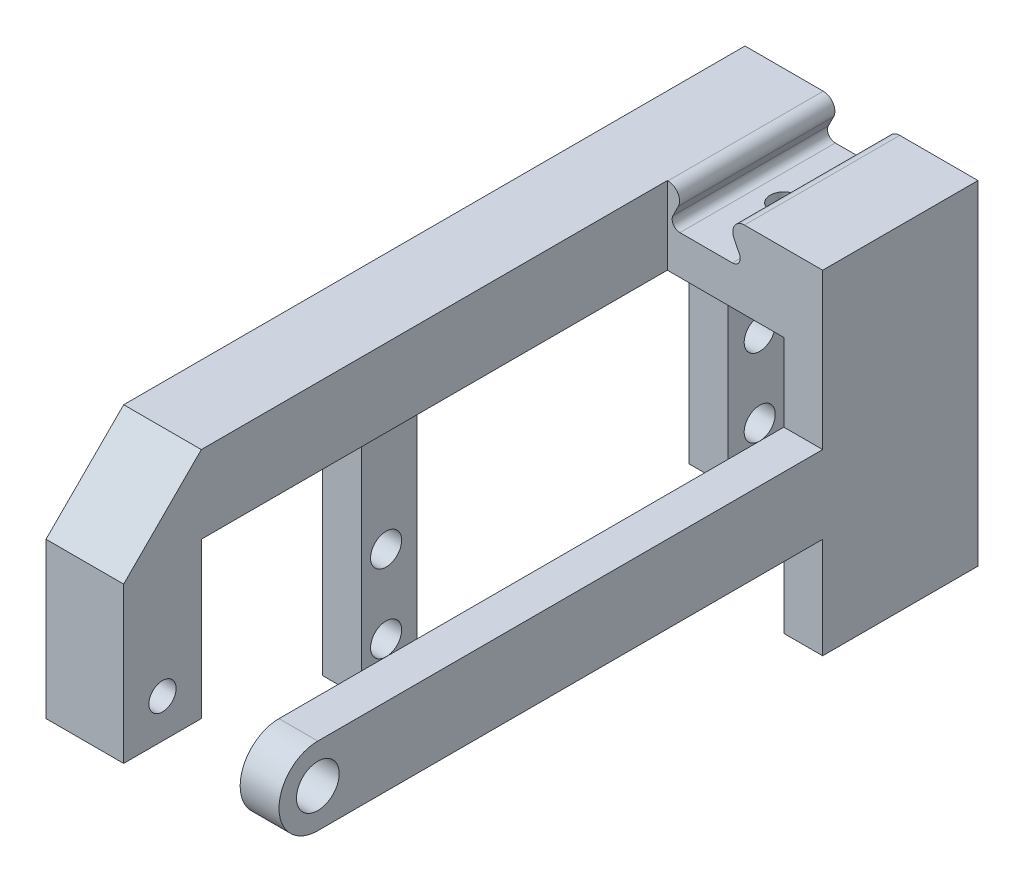
SolidWorks part; units mm, degrees
ref_plane "Plano frontal" through (0, 0, 0) normal (0, 0, 1) x (1, 0, 0)
ref_plane "Plano superior" through (0, 0, 0) normal (0, 1, 0) x (1, 0, 0)
ref_plane "Plano direito" through (0, 0, 0) normal (1, 0, 0) x (0, 0, -1)
sketch "Esboço1" plane through (0, 0, 0) normal (0, 0, 1) x (1, 0, 0)
  line L0 (-15, 45) -> (-15, 2)
  line L1 (-15, 2) -> (-10, 2)
  line L2 (-10, 2) -> (-10, 35)
  line L3 (-10, 35) -> (10, 35)
  line L4 (10, 35) -> (10, -35)
  line L5 (10, -35) -> (-15, -35)
  line L8 (-15, -35) -> (-15, -45)
  line L9 (-15, -45) -> (15, -45)
  line L10 (15, -45) -> (15, 45)
  line L11 (15, 45) -> (-15, 45)
  line L13 (-2.5, 45) -> (-5, 40)
  line L14 (-5, 40) -> (5, 40)
  line L15 (5, 40) -> (2.5, 45)
  point P12 (15, 0)
  point P13 (0, 45)
  point P21 (0, 40)
  dimension "D1" = 30
  dimension "D2" = 5
  dimension "D3" = 10
  dimension "D4" = 5
  dimension "D5" = 20
  dimension "D6" = 10
  dimension "D8" = 90
  dimension "D9" = 33
  dimension "D10" = 10
  dimension "D11" = 5
  dimension "D12" = 5
extrude "Ressalto-extrusão1" add sketch "Esboço1" along normal blind 80 contours L15 L14 L13 L11 L0 L1 L2 L3 L4 L5 L8 L9 L10
sketch "Esboço2" plane through (-15, 0, 0) normal (-1, 0, 0) x (0, 0, 1)
  line L0 (80, 2) -> (0, 2) construction
  line L1 (7.2, 2) -> (47.2, 2)
  line L2 (7.2, 2) -> (7.2, 35)
  line L3 (7.2, 35) -> (47.2, 35)
  line L4 (47.2, 2) -> (47.2, 35)
  line L5 (80, 45) -> (80, 2) construction
  line L6 (54.4, 2) -> (80, 2)
  line L7 (54.4, 2) -> (54.4, 35)
  line L8 (54.4, 35) -> (80, 35)
  line L9 (80, 2) -> (80, 35)
  line L10 (80, 45) -> (0, 45) construction
  dimension "D1" = 40
  dimension "D2" = 10
  dimension "D3" = 7.2
  dimension "D4" = 7.2
  dimension "D5" = 10
extrude "Corte-extrusão1" cut sketch "Esboço2" against normal blind 12
sketch "Esboço4" plane through (-10, 0, 0) normal (1, 0, 0) x (0, 0, -1)
  circle A0 centre (-3.1042, 17.0025) radius 2
  circle A1 centre (-3.1042, 7.0008) radius 2
  circle A2 centre (-51.2105, 17.0025) radius 2
  circle A3 centre (-51.2105, 7.0008) radius 2
extrude "Corte-extrusão3" cut sketch "Esboço4" against normal blind 12
sketch "Esboço6" plane through (-15, 0, 0) normal (-1, 0, 0) x (0, 0, 1)
  line L0 (80, 45) -> (90, 35)
  line L1 (80, 35) -> (90, 35)
  line L2 (80, 35) -> (80, 15)
  line L3 (80, 15) -> (90, 15)
  line L4 (90, 35) -> (90, 15)
  line M16 (80, 35) -> (80, 45)
  dimension "D1" = 10
  dimension "D2" = 20
extrude "Ressalto-extrusão2" add sketch "Esboço6" against normal blind 10 contours L4 L1 L2 L3 | L1 L0 M16
sketch "Esboço7" plane through (-15, 0, 0) normal (-1, 0, 0) x (0, 0, 1)
  line L0 (90, 35) -> (90, 15) construction
  line L1 (80, 15) -> (90, 15) construction
  circle A0 centre (85, 20) radius 1.75
  dimension "D1" = 3.5
  dimension "D2" = 5
  dimension "D3" = 5
extrude "Corte-extrusão4" cut sketch "Esboço7" against normal blind 15
sketch "Esboço8" plane through (-15, 0, 0) normal (-1, 0, 0) x (0, 0, 1)
  line L1 (85, 23.7528) -> (81.75, 21.8764)
  line L2 (81.75, 21.8764) -> (81.75, 18.1236)
  line L3 (81.75, 18.1236) -> (85, 16.2472)
  line L4 (85, 16.2472) -> (88.25, 18.1236)
  line L5 (88.25, 18.1236) -> (88.25, 21.8764)
  line L6 (88.25, 21.8764) -> (85, 23.7528)
  circle A0 centre (85, 20) radius 3.25 construction
  dimension "D1" = 6.5
extrude "Corte-extrusão5" cut sketch "Esboço8" against normal blind 5
sketch "Esboço10" plane through (15, 0, 0) normal (1, 0, 0) x (0, 0, -1)
  line L0 (-85, 25) -> (-80, 25)
  line L1 (-80, 35) -> (-80, 15) construction
  line L2 (-80, 25) -> (-80, 15)
  line L3 (-80, 15) -> (-85, 15)
  circle A0 centre (-85, 20) radius 2.75
  circle A1 centre (-85, 20) radius 5
  line M4 (-80, 45) -> (-80, -45)
  dimension "D1" = 5.5
extrude "Ressalto-extrusão3" add sketch "Esboço10" against normal blind 5 contours A1 L0 M4 | A1 A0 | A1 L3 L2
sketch "Esboço11" plane through (0, 0, 80) normal (0, 0, 1) x (1, 0, 0)
  line L1 (15, -45) -> (10, -45)
  line L2 (15, -45) -> (15, 15)
  line L3 (15, 15) -> (10, 15)
  line L4 (10, -45) -> (10, 15)
  line L5 (-5, 45) -> (15, 45)
  line L6 (-5, 45) -> (-5, 25)
  line L7 (-5, 25) -> (15, 25)
  line L8 (15, 45) -> (15, 25)
  line L9 (-15, -35) -> (10, -35)
  line L10 (-15, -35) -> (-15, -45)
  line L11 (-15, -45) -> (10, -45)
  line L12 (10, -35) -> (10, -45)
  line M1 (15, -45) -> (15, 15)
  line M2 (15, 15) -> (10, 15)
  line M3 (10, 15) -> (10, -35)
  line M4 (10, -35) -> (-15, -35)
  line M5 (-15, -35) -> (-15, -45)
  line M6 (-15, -45) -> (15, -45)
extrude "Corte-extrusão7" cut sketch "Esboço11" against normal blind 60 contours L8 L5 L6 L7 | L4 M6 M1 M2 M3 | L4 M6 M4 M5
sketch "Esboço13" plane through (0, 0, 20) normal (0, 0, 1) x (1, 0, 0)
  line L0 (15, -45) -> (15, 15) construction
  line L1 (-15, -45) -> (15, -45)
  line L2 (-15, -45) -> (-15, 2)
  line L3 (-15, 2) -> (15, 2)
  line L4 (15, -45) -> (15, 2)
  line L5 (-10, 2) -> (-15, 2) construction
extrude "Corte-extrusão9" cut sketch "Esboço13" against normal blind 168
fillet "Filete1" radius 1.5 2 edges at (2.5, 45, 10) (-2.5, 45, 10)
sketch "Esboço14" plane through (0, 40, 0) normal (0, 1, 0) x (1, 0, 0)
  line L0 (-5, -20) -> (5, -20) construction
  line L1 (15, -20) -> (15, 0) construction
  circle A0 centre (0, -10) radius 1.75
  dimension "D1" = 3.5
  dimension "D2" = 10
  dimension "D3" = 15
extrude "Corte-extrusão10" cut sketch "Esboço14" against normal blind 14.5
sketch "Esboço15" plane through (0, 35, 0) normal (0, -1, 0) x (1, 0, 0)
  line L1 (0, 13.7528) -> (-3.25, 11.8764)
  line L2 (-3.25, 11.8764) -> (-3.25, 8.1236)
  line L3 (-3.25, 8.1236) -> (0, 6.2472)
  line L4 (0, 6.2472) -> (3.25, 8.1236)
  line L5 (3.25, 8.1236) -> (3.25, 11.8764)
  line L6 (3.25, 11.8764) -> (0, 13.7528)
  circle A0 centre (0, 10) radius 3.25 construction
  dimension "D1" = 6.5
extrude "Corte-extrusão11" cut sketch "Esboço15" against normal blind 2.5
fillet "Filete2" radius 1 2 edges at (5, 40, 10) (-5, 40, 10)
